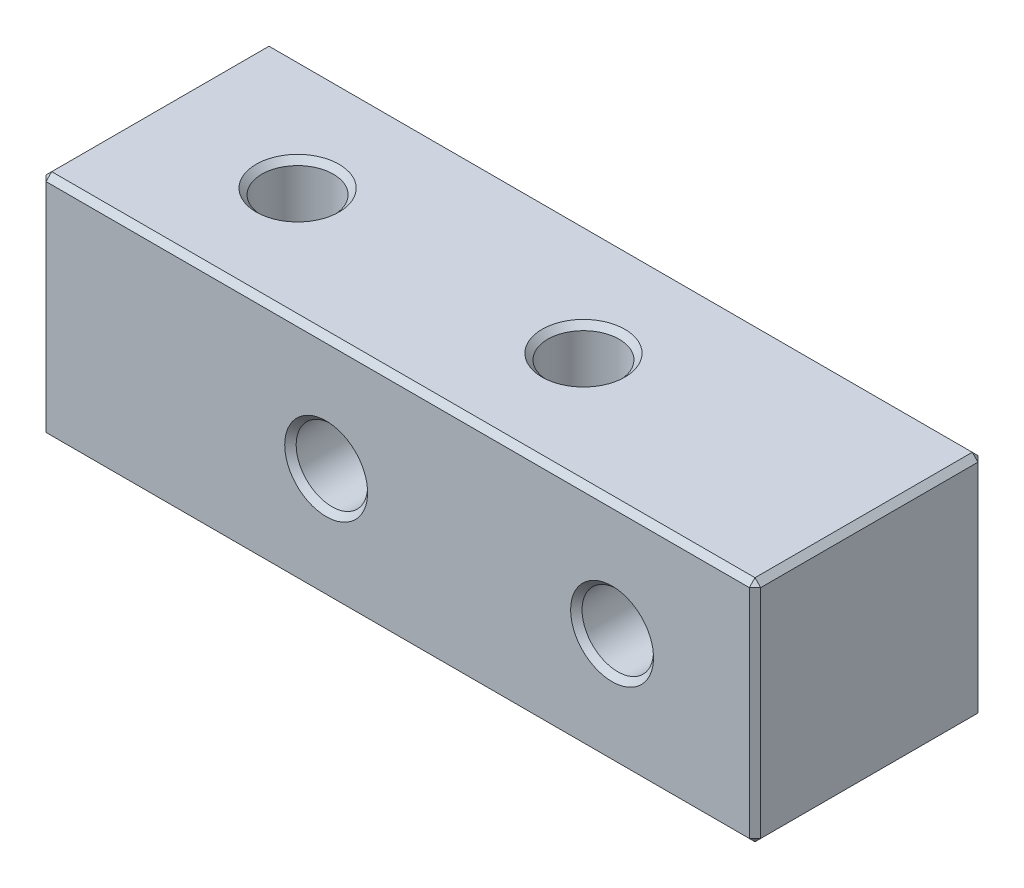
SolidWorks part; units mm, degrees
ref_plane "前视基准面" through (0, 0, 0) normal (0, 0, 1) x (1, 0, 0)
ref_plane "上视基准面" through (0, 0, 0) normal (0, 1, 0) x (1, 0, 0)
ref_plane "右视基准面" through (0, 0, 0) normal (1, 0, 0) x (0, 0, -1)
sketch "草图1" plane through (0, 0, 0) normal (0, 1, 0) x (1, 0, 0)
  line L1 (-12.5, 4) -> (12.5, 4)
  line L2 (-12.5, 4) -> (-12.5, -4)
  line L3 (-12.5, -4) -> (12.5, -4)
  line L4 (12.5, 4) -> (12.5, -4)
  line L5 (-12.5, 4) -> (12.5, -4) construction
  line L6 (-12.5, -4) -> (12.5, 4) construction
  point P0 (0, 0)
  dimension "D1" = 8
  dimension "D2" = 25
extrude "凸台-拉伸1" add sketch "草图1" along normal mid plane 8
hole_wizard "M3 螺纹孔1" positions "草图4" profile "草图6" tap size "M3" standard "GB" end condition through all
sketch "草图4" plane through (0, 4, 0) normal (0, 1, 0) x (1, 0, 0)
  line L0 (-12.5, 4) -> (-12.5, -4) construction
  line L1 (0, 0) -> (-50000, 0) construction
  point P0 (-7.5, 0)
  point P2 (2.5, 0)
  dimension "D1" = 5
  dimension "D2" = 10
sketch "草图6" plane through (-7.5, 4, 0) normal (1, 0, 0) x (0, 0, 1)
  line L0 (0, 0) -> (0, 8)
  line L1 (0, 8) -> (1.25, 8)
  line L2 (1.25, 8) -> (1.25, 0)
  line L5 (1.25, 0) -> (0, 0)
  line L11 (0, -6.35) -> (0, 107.95) construction
  dimension "通孔螺纹孔钻头直径" = 2.5
  dimension "通孔螺纹孔钻头深度" = 8
cosmetic thread "孔螺蚊线1" parameters "D2"=3
cosmetic thread "孔螺蚊线2" parameters "D2"=3
hole_wizard "M3 螺纹孔2" positions "草图7" profile "草图8" tap size "M3" standard "GB" end condition through all
sketch "草图7" plane through (0, 0, -4) normal (0, 0, -1) x (-1, 0, 0)
  line L0 (0, 0) -> (-50000, 0) construction
  line L1 (-12.5, 4) -> (-12.5, -4) construction
  point P0 (-7.5, 0)
  point P2 (2.5, 0)
  dimension "D1" = 5
  dimension "D2" = 10
sketch "草图8" plane through (7.5, 0, -4) normal (1, 0, 0) x (0, 1, 0)
  line L0 (0, 0) -> (0, 8)
  line L1 (0, 8) -> (1.25, 8)
  line L2 (1.25, 8) -> (1.25, 0)
  line L5 (1.25, 0) -> (0, 0)
  line L11 (0, -6.35) -> (0, 107.95) construction
  dimension "通孔螺纹孔钻头直径" = 2.5
  dimension "通孔螺纹孔钻头深度" = 8
cosmetic thread "孔螺蚊线3" parameters "D2"=3
cosmetic thread "孔螺蚊线4" parameters "D2"=3
chamfer "倒角1" distance 0.2 angle 45 20 edges at (2.5, -4, 1.25) (-7.5, -4, 1.25) (-3.75, 0, 4) (6.25, 0, 4) (2.5, 4, 1.25) (-7.5, 4, 1.25) (-12.5, -4, 0) (12.5, -4, 0) (-12.5, 0, 4) (0, -4, 4) (12.5, 0, 4) (0, 4, 4) (-12.5, 4, 0) (12.5, 4, 0) (12.5, 0, -4) (0, 4, -4) (-12.5, 0, -4) (0, -4, -4) (-3.75, 0, -4) (6.25, 0, -4)
